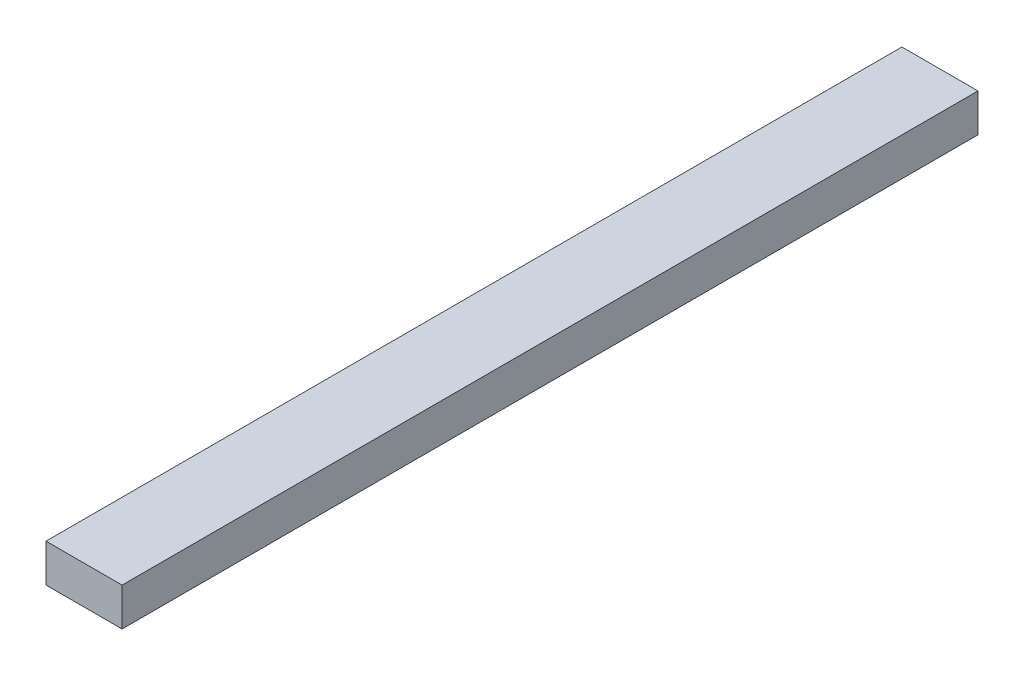
SolidWorks part; units mm, degrees
ref_plane "前视基准面" through (0, 0, 0) normal (0, 0, 1) x (1, 0, 0)
ref_plane "上视基准面" through (0, 0, 0) normal (0, 1, 0) x (1, 0, 0)
ref_plane "右视基准面" through (0, 0, 0) normal (1, 0, 0) x (0, 0, -1)
sketch "草图1" plane through (0, 0, 0) normal (0, 0, 1) x (1, 0, 0)
  line L1 (-20, -10) -> (20, -10)
  line L2 (-20, -10) -> (-20, 10)
  line L3 (-20, 10) -> (20, 10)
  line L4 (20, -10) -> (20, 10)
  line L5 (-20, -10) -> (20, 10) construction
  line L6 (-20, 10) -> (20, -10) construction
  point P0 (0, 0)
  dimension "D1" = 40
  dimension "D2" = 20
extrude "凸台-拉伸1" add sketch "草图1" along normal blind 450
